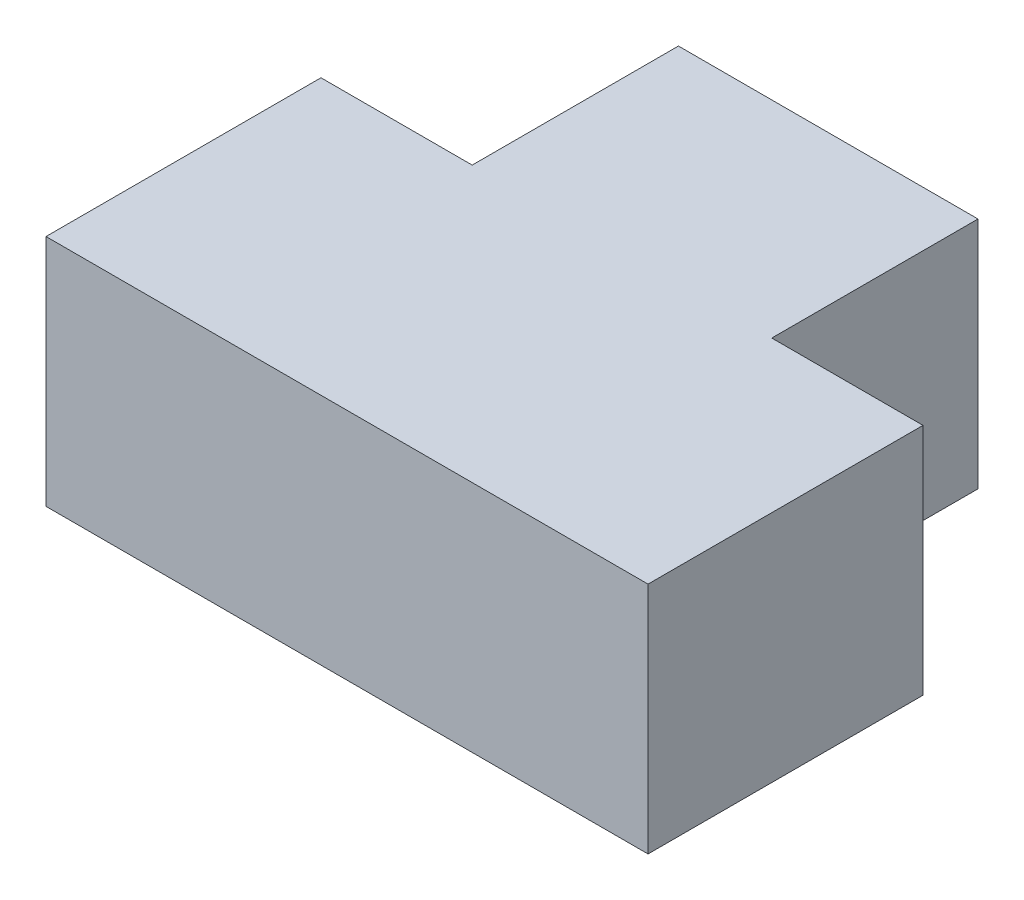
SolidWorks part; units mm, degrees
ref_plane "Спереди" through (0, 0, 0) normal (0, 0, 1) x (1, 0, 0)
ref_plane "Сверху" through (0, 0, 0) normal (0, 1, 0) x (1, 0, 0)
ref_plane "Справа" through (0, 0, 0) normal (1, 0, 0) x (0, 0, -1)
sketch "Эскиз1" plane through (0, 0, 0) normal (0, 1, 0) x (1, 0, 0)
  line L5 (2.379, 0) -> (-2.379, 0) construction
  line L6 (2.379, 0) -> (2.379, -4) construction
  line L7 (2.379, -4) -> (-2.379, -4)
  line L8 (-2.379, 0) -> (-2.379, -4) construction
  line L10 (-2.379, -4) -> (-4.379, -4)
  line L11 (-4.379, -4) -> (-4.379, 0)
  line L12 (-4.379, 0) -> (-2.379, 0)
  line L14 (0, 0) -> (0, -4) construction
  line L15 (4.379, 0) -> (2.379, 0)
  line L16 (4.379, -4) -> (4.379, 0)
  line L17 (2.379, -4) -> (4.379, -4)
  line L19 (2.379, 0) -> (2.379, 3)
  line L20 (2.379, 3) -> (-2.379, 3)
  line L21 (-2.379, 3) -> (-2.379, 0)
  line L22 (-2.379, 1.5) -> (-2.379, 0) construction
  line L23 (-2.379, 0) -> (2.621, 0) construction
  point P6 (-2.3171, 1.5)
  point P7 (-2.3597, 0)
  point P8 (-2.3597, 0)
  point P9 (-2.379, 0)
  point P10 (-2.379, 0)
  point P16 (2.379, 0)
  dimension "D1" = 4
  dimension "D2" = 2
  dimension "D3" = 3
extrude "Бобышка-Вытянуть1" add sketch "Эскиз1" along normal up to surface (3.4 mm away)
sketch "Эскиз2" plane through (0, 0, 0) normal (0, 1, 0) x (1, 0, 0)
  line L0 (2.379, 0) -> (4.379, 0) construction
  line L1 (2.579, 0) -> (2.179, 0)
  line L2 (2.579, 0) -> (2.579, 3)
  line L3 (2.579, 3) -> (2.179, 3)
  line L4 (2.179, 0) -> (2.179, 3)
  line L5 (-2.379, 3) -> (2.379, 3) construction
  line L6 (0, 0) -> (0, 3) construction
  line L7 (-2.179, 0) -> (-2.179, 3)
  line L8 (-2.579, 3) -> (-2.179, 3)
  line L9 (-2.579, 0) -> (-2.579, 3)
  line L10 (-2.579, 0) -> (-2.179, 0)
  point P8 (2.379, 3)
  point P9 (-2.379, 3)
  dimension "D1" = 0.2
extrude "Вырез-Вытянуть1" cut sketch "Эскиз2" along normal through all
